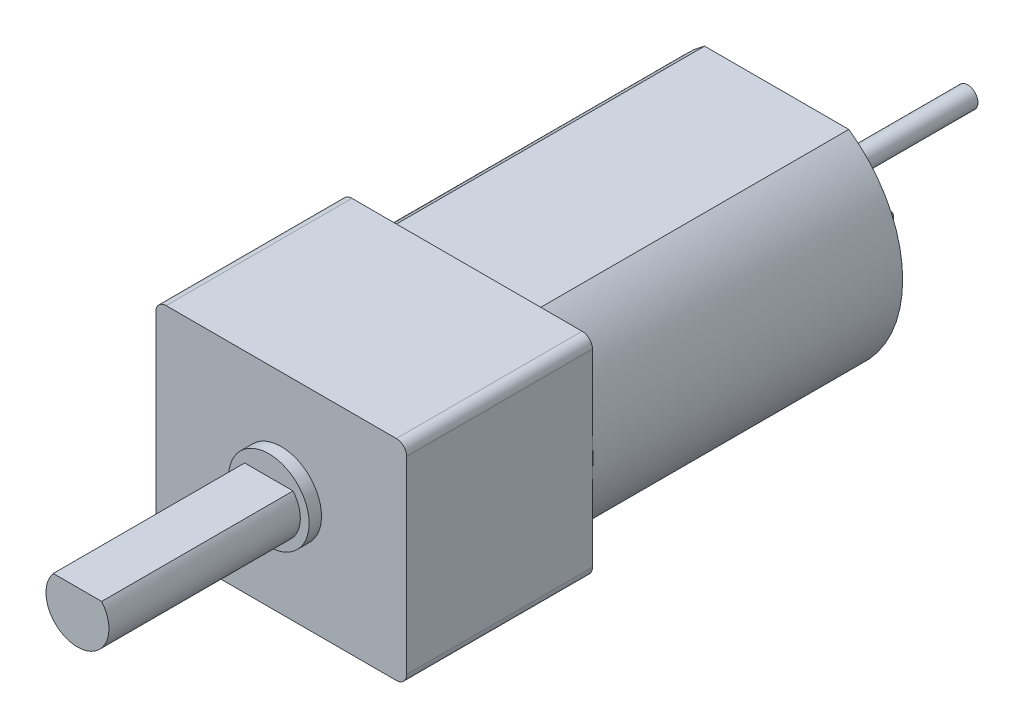
SolidWorks part; units mm, degrees
ref_plane "Front Plane" through (0, 0, 0) normal (0, 0, 1) x (1, 0, 0)
ref_plane "Top Plane" through (0, 0, 0) normal (0, 1, 0) x (1, 0, 0)
ref_plane "Right Plane" through (0, 0, 0) normal (1, 0, 0) x (0, 0, -1)
sketch "Sketch1" plane through (0, 0, 0) normal (0, 0, 1) x (1, 0, 0)
  line L0 (0, 5.075) -> (0, -5.075) construction
  line L1 (0, -5.075) -> (0, 0) construction
  line L7 (-6.075, 5.075) -> (6.075, 5.075)
  line L8 (-6.075, 5.075) -> (-6.075, -5.075)
  line L9 (-6.075, -5.075) -> (6.075, -5.075)
  line L10 (6.075, 5.075) -> (6.075, -5.075)
  dimension "D1" = 10.15
  dimension "D3" = 12.15
extrude "Extrude2" add sketch "Sketch1" against normal blind 9
sketch "Sketch11" plane through (0, 0, 0) normal (0, 0, 1) x (1, 0, 0)
  line L0 (0, 5.075) -> (0, -5.075) construction
  line L1 (6.075, 5.075) -> (-6.075, 5.075) construction
  line L2 (-6.075, -5.075) -> (6.075, -5.075) construction
  line L3 (-6.075, 0) -> (0, 0) construction
  line L4 (-6.075, 5.075) -> (-6.075, -5.075) construction
  line L5 (0, 0) -> (6.075, 0) construction
  line L6 (6.075, -5.075) -> (6.075, 5.075) construction
  circle A0 centre (0, 0) radius 1.95
  dimension "D1" = 3.9
extrude "Extrude5" add sketch "Sketch11" along normal blind 0.6
sketch "Sketch12" plane through (0, 0, 0.6) normal (0, 0, 1) x (1, 0, 0)
  line L0 (0, 0.975) -> (0, -1.525) construction
  line L1 (0, 0.975) -> (0, -1.525) construction
  line L2 (-1.1726, 0.975) -> (1.1726, 0.975)
  arc A0 (-1.1726, 0.975) -> (1.1726, 0.975) centre (0, 0) ccw
  dimension "D1" = 3.05
  dimension "D2" = 2.3452
extrude "Extrude6" add sketch "Sketch12" along normal blind 9.27
sketch "Sketch13" plane through (0, 0, -9) normal (0, 0, -1) x (-1, 0, 0)
  line L0 (0, 5.075) -> (0, -5.075) construction
  line L1 (-6.075, 5.075) -> (6.075, 5.075) construction
  line L2 (6.075, -5.075) -> (-6.075, -5.075) construction
  line L3 (-6.075, -5.075) -> (-6.075, 5.075) construction
  line L4 (-6.075, 0) -> (0, 0) construction
  line L5 (0, 0) -> (6.075, 0) construction
  line L6 (6.075, 5.075) -> (6.075, -5.075) construction
  line L7 (0, 5) -> (0, -5) construction
  line L8 (-3.4943, 5) -> (3.4943, 5)
  line L10 (-3.4943, -5) -> (3.4943, -5)
  line L12 (0, -5) -> (0, 0) construction
  arc A0 (-3.4943, 5) -> (-3.4943, -5) centre (0, 0) ccw
  arc A1 (3.4943, -5) -> (3.4943, 5) centre (0, 0) ccw
  dimension "D1" = 12.2
  dimension "D2" = 6.9886
  dimension "D3" = 6.9886
extrude "Extrude7" add sketch "Sketch13" along normal blind 15
sketch "Sketch14" plane through (0, 0, -24) normal (0, 0, -1) x (-1, 0, 0)
  line L0 (0, 5) -> (0, -5) construction
  line L1 (3.4943, 5) -> (-3.4943, 5) construction
  line L2 (-3.4943, -5) -> (3.4943, -5) construction
  line L3 (0, -5) -> (0, 0) construction
  circle A0 centre (0, 0) radius 2.5
  dimension "D1" = 5
extrude "Extrude8" add sketch "Sketch14" along normal blind 1.5
sketch "Sketch16" plane through (0, 0, -24) normal (0, 0, -1) x (-1, 0, 0)
  line L0 (0, 2.5) -> (0, -2.5) construction
  line L1 (3.35, 0.75) -> (3.65, 0.75)
  line L2 (3.35, 0.75) -> (3.35, -0.75)
  line L3 (3.35, -0.75) -> (3.65, -0.75)
  line L4 (3.65, 0.75) -> (3.65, -0.75)
  line L5 (0, -2.5) -> (0, 0) construction
  line L6 (3.5, 0.75) -> (3.5, -0.75) construction
  line L7 (3.5, -0.75) -> (3.5, 0) construction
  circle A0 centre (0, 0) radius 2.5 construction
  dimension "D1" = 0.3
  dimension "D2" = 1.5
  dimension "D3" = 3.5
extrude "Extrude10" add sketch "Sketch16" along normal blind 2
fillet "Fillet1" radius 0.3 2 edges at (-3.5, -0.75, -26) (-3.5, 0.75, -26)
mirror "Mirror1" about plane through (0, 0, 0) normal (1, 0, 0) of "Extrude10", "Fillet1"
fillet "Fillet2" radius 0.5 4 edges at (6.075, -5.075, -4.5) (-6.075, -5.075, -4.5) (-6.075, 5.075, -4.5) (6.075, 5.075, -4.5)
fillet "Fillet3" radius 0.3 1 edges at (-2.5, 0, -25.5)
sketch "Sketch17" plane through (0, 0, -25.5) normal (0, 0, -1) x (-1, 0, 0)
  circle A0 centre (0, 0) radius 0.5
extrude "Extrude11" add sketch "Sketch17" along normal blind 7.75
